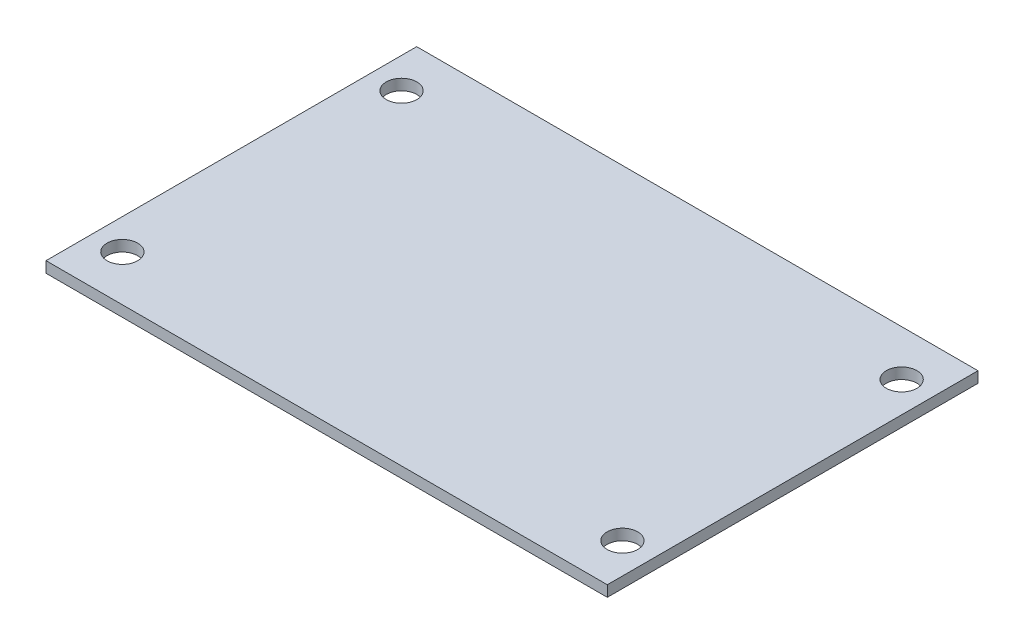
SolidWorks part; units mm, degrees
material "6061-T6 (SS)"
ref_plane "Alzado" through (0, 0, 0) normal (0, 0, 1) x (1, 0, 0)
ref_plane "Planta" through (0, 0, 0) normal (0, 1, 0) x (1, 0, 0)
ref_plane "Vista lateral" through (0, 0, 0) normal (1, 0, 0) x (0, 0, -1)
sketch "Croquis1" plane through (0, 0, 0) normal (0, 1, 0) x (1, 0, 0)
  line L1 (-38.5, 25.425) -> (38.5, 25.425)
  line L2 (-38.5, 25.425) -> (-38.5, -25.425)
  line L3 (-38.5, -25.425) -> (38.5, -25.425)
  line L4 (38.5, 25.425) -> (38.5, -25.425)
  line L5 (-38.5, 25.425) -> (38.5, -25.425) construction
  line L6 (-38.5, -25.425) -> (38.5, 25.425) construction
  point P0 (0, 0)
  dimension "D1" = 77
  dimension "D2" = 50.85
extrude "Saliente-Extruir1" add sketch "Croquis1" along normal blind 1.5
sketch "Croquis2" plane through (0, 1.5, 0) normal (0, 1, 0) x (1, 0, 0)
  line L1 (-34.3, 19.15) -> (34.3, 19.15) construction
  line L2 (-34.3, 19.15) -> (-34.3, -19.15) construction
  line L3 (-34.3, -19.15) -> (34.3, -19.15) construction
  line L4 (34.3, 19.15) -> (34.3, -19.15) construction
  line L5 (-34.3, 19.15) -> (34.3, -19.15) construction
  line L6 (-34.3, -19.15) -> (34.3, 19.15) construction
  circle A0 centre (-34.3, 19.15) radius 2.1
  circle A1 centre (34.3, 19.15) radius 2.1
  circle A2 centre (34.3, -19.15) radius 2.1
  circle A3 centre (-34.3, -19.15) radius 2.1
  point P0 (0, 0)
  dimension "D1" = 68.6
  dimension "D3" = 4.2
  dimension "D2" = 38.3
extrude "Cortar-Extruir1" cut sketch "Croquis2" against normal through all
